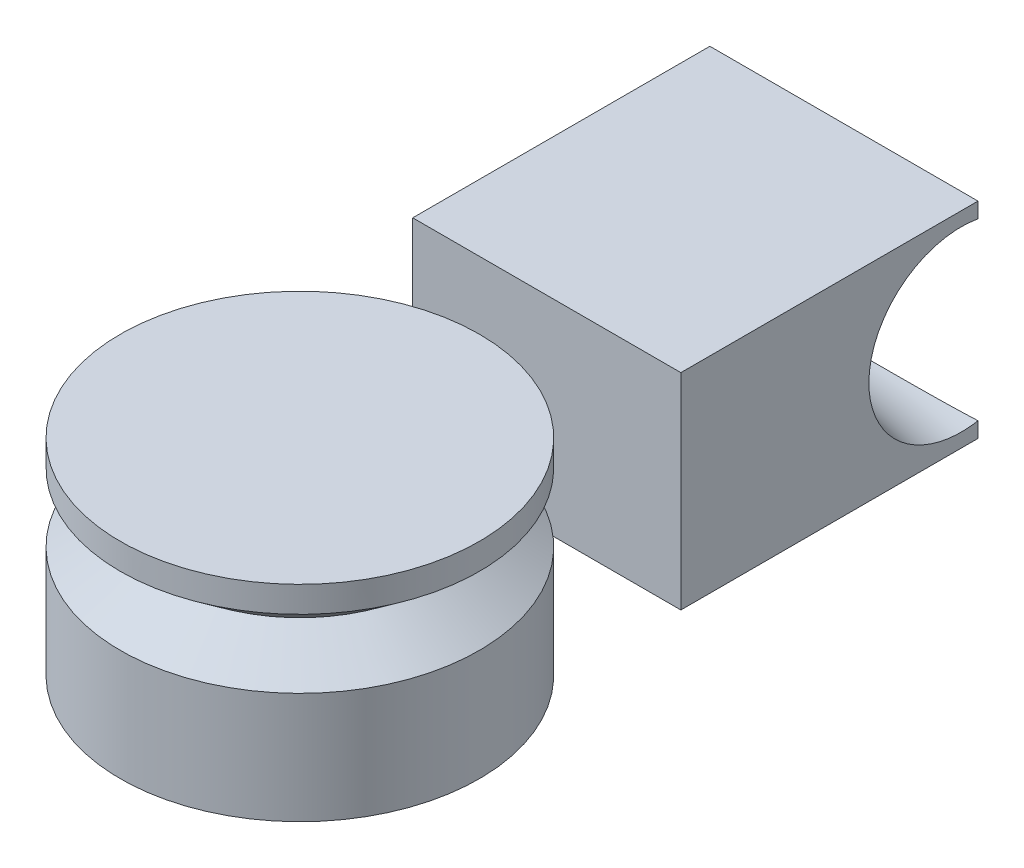
SolidWorks part; units mm, degrees
ref_plane "Front Plane" through (0, 0, 0) normal (0, 0, 1) x (1, 0, 0)
ref_plane "Top Plane" through (0, 0, 0) normal (0, 1, 0) x (1, 0, 0)
ref_plane "Right Plane" through (0, 0, 0) normal (1, 0, 0) x (0, 0, -1)
sketch "Sketch1" plane through (0, 0, 0) normal (0, 0, 1) x (1, 0, 0)
  line L1 (0, 0) -> (58.687, 0)
  line L2 (0, 0) -> (0, 67.2093)
  line L3 (0, 67.2093) -> (58.687, 67.2093)
  line L4 (58.687, 0) -> (58.687, 67.2093)
revolve "Revolve1" add sketch "Sketch1" angle 360 about L2
sketch "Sketch2" plane through (0, 0, 0) normal (0, 1, 0) x (1, 0, 0)
  line L0 (0, 0) -> (0, 80.7292) construction
  line L1 (-43.8303, 177.8668) -> (43.8303, 177.8668)
  line L2 (-43.8303, 177.8668) -> (-43.8303, 80.7292)
  line L3 (-43.8303, 80.7292) -> (43.8303, 80.7292)
  line L4 (43.8303, 177.8668) -> (43.8303, 80.7292)
extrude "Boss-Extrude1" add sketch "Sketch2" along normal up to surface (67.2093 mm away) separate body up to face at (0, 67.2093, -58.687)
sketch "Sketch3" plane through (0, 0, 0) normal (1, 0, 0) x (0, 0, -1)
  line L0 (177.8668, 67.2093) -> (177.8668, 0) construction
  line L1 (62.8461, 61.907) -> (43.0032, 46.6592)
  line L2 (43.0032, 46.6592) -> (62.8461, 33.6046)
  line L3 (62.8461, 33.6046) -> (62.8461, 61.907)
  circle A0 centre (177.8668, 33.6046) radius 29.0709
revolve "Cut-Revolve1" cut sketch "Sketch3" angle 360 about axis through (0, 0, 0) along (0, -1, 0)
